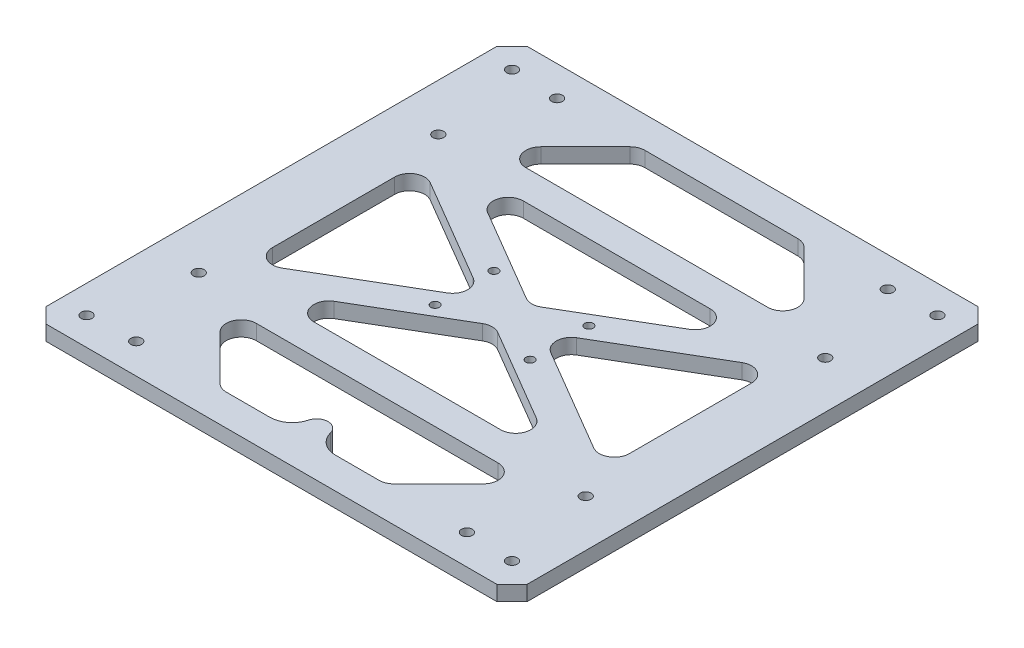
SolidWorks part; units mm, degrees
ref_plane "Front Plane" through (0, 0, 0) normal (0, 0, 1) x (1, 0, 0)
ref_plane "Top Plane" through (0, 0, 0) normal (0, 1, 0) x (1, 0, 0)
ref_plane "Right Plane" through (0, 0, 0) normal (1, 0, 0) x (0, 0, -1)
sketch "Sketch1" plane through (0, 0, 0) normal (0, 1, 0) x (1, 0, 0)
  line L0 (0, 196.85) -> (6.35, 203.2)
  line L1 (6.35, 0) -> (196.85, 0)
  line L2 (0, 6.35) -> (0, 196.85)
  line L3 (6.35, 203.2) -> (196.85, 203.2)
  line L4 (203.2, 6.35) -> (203.2, 196.85)
  line L5 (196.85, 203.2) -> (203.2, 196.85)
  line L6 (196.85, 0) -> (203.2, 6.35)
  line L7 (0, 6.35) -> (6.35, 0)
  point P0 (0, 0)
  point P1 (203.2, 203.2)
  point P2 (0, 203.2)
  point P3 (203.2, 0)
  dimension "D1" = 203.2
  dimension "D2" = 203.2
extrude "Boss-Extrude1" add sketch "Sketch1" along normal blind 6.35
sketch "Sketch3" plane through (0, 6.35, 0) normal (0, 1, 0) x (1, 0, 0)
  line L0 (6.35, 0) -> (196.85, 0) construction
  line L1 (0, 196.85) -> (0, 6.35) construction
  line L2 (203.2, 6.35) -> (203.2, 196.85) construction
  line L3 (196.85, 203.2) -> (6.35, 203.2) construction
  circle A0 centre (11.7373, 11.7373) radius 2.286
  circle A1 centre (191.4627, 11.7373) radius 2.286
  circle A2 centre (191.4627, 191.4627) radius 2.286
  circle A3 centre (11.7373, 191.4627) radius 2.286
  dimension "D1" = 2
  dimension "D3" = 4.572
  dimension "D4" = 11.7373
  dimension "D5" = 11.7373
  dimension "D6" = 11.7373
  dimension "D7" = 11.7373
  dimension "D8" = 11.7373
  dimension "D2" = 2
extrude "Cut-Extrude2" cut sketch "Sketch3" against normal through all
sketch "Sketch4" plane through (0, 6.35, 0) normal (0, 1, 0) x (1, 0, 0)
  line L0 (0, 196.85) -> (0, 6.35) construction
  line L1 (19.8692, 152.1955) -> (183.3308, 152.1955) construction
  line L2 (19.8692, 152.1955) -> (19.8692, 51.0045) construction
  line L3 (19.8692, 51.0045) -> (183.3308, 51.0045) construction
  line L4 (183.3308, 152.1955) -> (183.3308, 51.0045) construction
  line L5 (196.85, 203.2) -> (6.35, 203.2) construction
  line L6 (16.6942, 140.0403) -> (66.6884, 190.0345)
  line L7 (136.5116, 190.0345) -> (66.6884, 190.0345)
  line L8 (136.5116, 190.0345) -> (186.5058, 140.0403)
  line L9 (186.5058, 63.1597) -> (136.5116, 13.1655)
  line L10 (186.5058, 140.0403) -> (186.5058, 63.1597)
  line L11 (136.5116, 13.1655) -> (66.6884, 13.1655)
  line L12 (66.6884, 13.1655) -> (16.6942, 63.1597)
  line L13 (16.6942, 63.1597) -> (16.6942, 140.0403)
  circle A0 centre (19.8692, 152.1955) radius 2.286
  circle A1 centre (183.3308, 152.1955) radius 2.286
  circle A2 centre (183.3308, 51.0045) radius 2.286
  circle A3 centre (19.8692, 51.0045) radius 2.286
  point P6 (0, 101.6)
  point P7 (19.8692, 101.6)
  point P10 (101.6, 203.2)
  point P11 (101.6, 152.1955)
  dimension "D3" = 4.572
  dimension "D5" = 6.35
  dimension "D7" = 6.35
  dimension "D1" = 163.4617
  dimension "D2" = 101.1911
  dimension "D4" = 6.35
  dimension "D6" = 6.35
  dimension "D8" = 6.35
extrude "Cut-Extrude3" cut sketch "Sketch4" against normal through all
sketch "Sketch5" plane through (0, 6.35, 0) normal (0, 1, 0) x (1, 0, 0)
  line L0 (19.8692, 51.0045) -> (183.3308, 51.0045) construction
  line L1 (183.3308, 51.0045) -> (183.3308, 152.1955) construction
  line L2 (183.3308, 152.1955) -> (19.8692, 152.1955) construction
  line L3 (19.8692, 152.1955) -> (19.8692, 51.0045) construction
  line L4 (189.6808, 158.5455) -> (13.5192, 158.5455)
  line L5 (13.5192, 158.5455) -> (13.5192, 44.6545)
  line L6 (13.5192, 44.6545) -> (189.6808, 44.6545)
  line L7 (189.6808, 44.6545) -> (189.6808, 158.5455)
  line L8 (141.0736, 145.8455) -> (62.1264, 145.8455)
  line L9 (26.2192, 127.3922) -> (26.2192, 75.8078)
  line L10 (62.1264, 57.3545) -> (141.0736, 57.3545)
  line L11 (176.9808, 75.8078) -> (176.9808, 127.3922)
  line L12 (26.2192, 57.3545) -> (176.9808, 145.8455) construction
  line L13 (176.9808, 57.3545) -> (26.2192, 145.8455) construction
  line L14 (58.912, 69.1808) -> (98.3856, 92.3502)
  line L15 (167.4165, 70.3314) -> (123.4744, 96.1237)
  line L16 (35.7835, 70.3314) -> (79.7256, 96.1237)
  line L17 (144.288, 69.1808) -> (104.8144, 92.3502)
  line L18 (180.1952, 62.8308) -> (29.4335, 151.3219) construction
  line L19 (173.7665, 51.8781) -> (23.0048, 140.3692) construction
  line L20 (23.0048, 62.8308) -> (173.7665, 151.3219) construction
  line L21 (29.4335, 51.8781) -> (180.1952, 140.3692) construction
  line L22 (26.2192, 57.3545) -> (176.9808, 57.3545) construction
  line L23 (176.9808, 57.3545) -> (176.9808, 145.8455) construction
  line L24 (176.9808, 145.8455) -> (26.2192, 145.8455) construction
  line L25 (26.2192, 145.8455) -> (26.2192, 57.3545) construction
  line L26 (79.7256, 107.0763) -> (35.7835, 132.8686)
  line L27 (104.8144, 110.8498) -> (144.288, 134.0192)
  line L28 (123.4744, 107.0763) -> (167.4165, 132.8686)
  line L29 (98.3856, 110.8498) -> (58.912, 134.0192)
  circle A0 centre (183.3308, 51.0045) radius 2.286 construction
  circle A1 centre (183.3308, 152.1955) radius 2.286 construction
  circle A2 centre (19.8692, 152.1955) radius 2.286 construction
  circle A3 centre (19.8692, 51.0045) radius 2.286 construction
  circle A4 centre (183.3308, 51.0045) radius 2.286
  circle A5 centre (183.3308, 152.1955) radius 2.286
  circle A6 centre (19.8692, 152.1955) radius 2.286
  circle A7 centre (19.8692, 51.0045) radius 2.286
  arc A8 (58.912, 134.0192) -> (62.1264, 145.8455) centre (62.1264, 139.4955) cw
  arc A9 (144.288, 134.0192) -> (141.0736, 145.8455) centre (141.0736, 139.4955) ccw
  arc A10 (167.4165, 132.8686) -> (176.9808, 127.3922) centre (170.6308, 127.3922) cw
  arc A11 (123.4744, 107.0763) -> (123.4744, 96.1237) centre (126.6888, 101.6) ccw
  arc A12 (167.4165, 70.3314) -> (176.9808, 75.8078) centre (170.6308, 75.8078) ccw
  arc A13 (144.288, 69.1808) -> (141.0736, 57.3545) centre (141.0736, 63.7045) cw
  arc A14 (104.8144, 92.3502) -> (98.3856, 92.3502) centre (101.6, 86.8739) ccw
  arc A15 (79.7256, 107.0763) -> (79.7256, 96.1237) centre (76.5112, 101.6) cw
  arc A16 (35.7835, 132.8686) -> (26.2192, 127.3922) centre (32.5692, 127.3922) ccw
  arc A17 (35.7835, 70.3314) -> (26.2192, 75.8078) centre (32.5692, 75.8078) cw
  arc A18 (58.912, 69.1808) -> (62.1264, 57.3545) centre (62.1264, 63.7045) ccw
  arc A19 (98.3856, 110.8498) -> (104.8144, 110.8498) centre (101.6, 116.3261) ccw
  dimension "D5" = 6.35
  dimension "D6" = 6.35
  dimension "D1" = 6.35
  dimension "D3" = 6.35
  dimension "D2" = 6.35
  dimension "D4" = 6.35
extrude "Boss-Extrude2" add sketch "Sketch5" against normal up to surface (6.35 mm away) up to face at (183.3308, 0, -149.9095)
fillet "Fillet1" radius 6.35 8 edges at (136.5116, 3.175, -190.0345) (66.6884, 3.175, -190.0345) (35.1994, 3.175, -158.5455) (168.0006, 3.175, -158.5455) (66.6884, 3.175, -13.1655) (35.1994, 3.175, -44.6545) (136.5116, 3.175, -13.1655) (168.0006, 3.175, -44.6545)
sketch "Sketch6" plane through (0, 6.35, 0) normal (0, 1, 0) x (1, 0, 0)
  line L0 (6.35, 0) -> (196.85, 0) construction
  line L1 (69.3186, 13.1655) -> (133.8814, 13.1655) construction
  line L2 (87.7184, 13.1655) -> (115.4816, 13.1655)
  circle A0 centre (101.6, 19.05) radius 2.286 construction
  arc A1 (106.2681, 20.2742) -> (96.9319, 20.2742) centre (101.6, 19.05) ccw
  arc A2 (87.7184, 13.1655) -> (96.9319, 20.2742) centre (87.7184, 22.6905) ccw
  arc A3 (106.2681, 20.2742) -> (115.4816, 13.1655) centre (115.4816, 22.6905) ccw
  point P7 (101.6, 0)
  dimension "D1" = 19.05
  dimension "D2" = 4.572
  dimension "D3" = 2.54
  dimension "D4" = 19.05
extrude "Boss-Extrude3" add sketch "Sketch6" against normal up to surface (6.35 mm away) up to face at (101.6, 0, -26.9283)
sketch "Sketch8" plane through (0, 0, 0) normal (0, 1, 0) x (1, 0, 0)
  circle A0 centre (101.6, 19.05) radius 4.826
  circle A1 centre (101.6, 19.05) radius 2.286
  arc A2 (106.2681, 20.2742) -> (96.9319, 20.2742) centre (101.6, 19.05) ccw construction
  dimension "D1" = 4.572
extrude "Boss-Extrude4" add sketch "Sketch8" against normal blind 6.35
sketch "Sketch9" plane through (0, 0, 0) normal (0, 1, 0) x (1, 0, 0)
  line L0 (80.0033, 114.9695) -> (123.1967, 88.2305) construction
  line L1 (123.1967, 114.9695) -> (80.0033, 88.2305) construction
  circle A0 centre (121.6633, 114.0202) radius 1.8034 construction
  circle A1 centre (81.5367, 114.0202) radius 1.8034 construction
  circle A2 centre (81.5367, 89.1798) radius 1.8034 construction
  circle A3 centre (121.6633, 89.1798) radius 1.8034 construction
  circle A4 centre (81.5367, 114.0202) radius 3.8354
  circle A5 centre (121.6633, 114.0202) radius 3.8354
  circle A6 centre (121.6633, 89.1798) radius 3.8354
  circle A7 centre (81.5367, 89.1798) radius 3.8354
  point P8 (101.6, 101.6)
  dimension "D1" = 3.6068
  dimension "D2" = 50.8
  dimension "D3" = 116.481
  dimension "D4" = 2.032
extrude "Cut-Extrude4" cut sketch "Sketch9" along normal offset from surface (3.81 mm away) 2.54 up to face at (101.6, 6.35, -23.5639)
sketch "Sketch10" plane through (0, 3.81, 0) normal (0, -1, 0) x (-1, 0, 0)
  circle A26 centre (-81.5367, 114.0202) radius 1.8034
  circle A27 centre (-121.6633, 114.0202) radius 1.8034
  circle A28 centre (-121.6633, 89.1798) radius 1.8034
  circle A29 centre (-81.5367, 89.1798) radius 1.8034
  dimension "D1" = 3.6068
extrude "Cut-Extrude5" cut sketch "Sketch10" against normal through all
sketch "Sketch11" plane through (0, 0, 0) normal (0, -1, 0) x (1, 0, 0)
  line L0 (0, -196.85) -> (0, -6.35) construction
  line L1 (6.35, 0) -> (196.85, 0) construction
  line L2 (196.85, -203.2) -> (6.35, -203.2) construction
  line L3 (203.2, -6.35) -> (203.2, -196.85) construction
  circle A0 centre (31.75, -12.7) radius 2.286
  circle A1 centre (171.45, -12.7) radius 2.286
  circle A2 centre (171.45, -190.5) radius 2.286
  circle A3 centre (31.75, -190.5) radius 2.286
  dimension "D1" = 4.572
  dimension "D6" = 12.7
  dimension "D7" = 31.75
  dimension "D8" = 31.75
  dimension "D2" = 31.75
  dimension "D3" = 12.7
  dimension "D4" = 2
  dimension "D5" = 2
extrude "Cut-Extrude6" cut sketch "Sketch11" against normal through all and the other way through all
